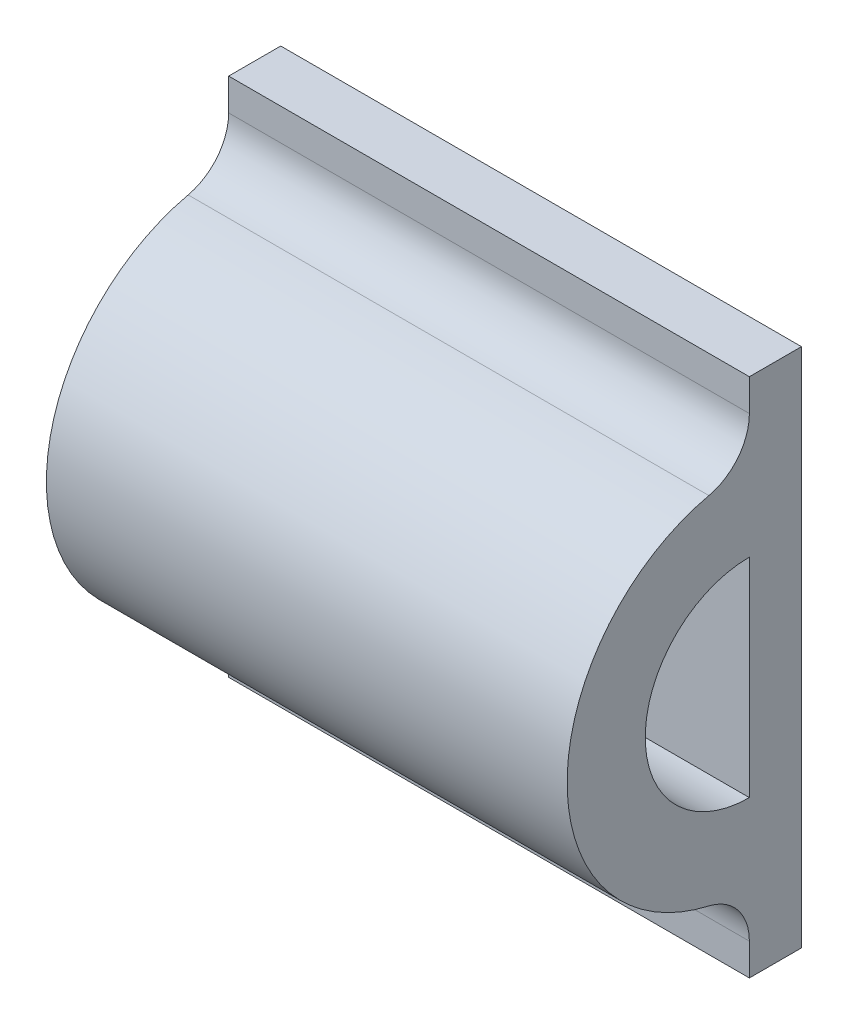
SolidWorks part; units mm, degrees
ref_plane "Alzado" through (0, 0, 0) normal (0, 0, 1) x (1, 0, 0)
ref_plane "Planta" through (0, 0, 0) normal (0, 1, 0) x (1, 0, 0)
ref_plane "Vista lateral" through (0, 0, 0) normal (1, 0, 0) x (0, 0, -1)
sketch "Croquis1" plane through (0, 0, 0) normal (0, 0, 1) x (1, 0, 0)
  line L1 (5, 5) -> (-5, 5)
  line L2 (5, 5) -> (5, -5)
  line L3 (5, -5) -> (-5, -5)
  line L4 (-5, 5) -> (-5, -5)
  line L5 (0, -5) -> (0, 5) construction
  line L6 (5, 0) -> (-5, 0) construction
  point P0 (0, 0)
  dimension "D1" = 10
  dimension "D2" = 10
extrude "Saliente-Extruir1" add sketch "Croquis1" along normal blind 1
sketch "Croquis2" plane through (0, 0, 0) normal (1, 0, 0) x (0, 0, -1)
  line L0 (-1, -5) -> (-1, 5) construction
  line L1 (-1, 3.5) -> (-1, 2)
  line L2 (-1, -2) -> (-1, -3.5)
  arc A0 (-1, -3.5) -> (-1, 3.5) centre (-1, 0) cw
  arc A1 (-1, -2) -> (-1, 2) centre (-1, 0) cw
extrude "Saliente-Extruir2" add sketch "Croquis2" against normal through all from surface at 5 starting at face at (5, 0, 0.5)
fillet "Redondeo2" radius 1 1 edges at (0, 3.5, 1)
fillet "Redondeo3" radius 1 1 edges at (0, -3.5, 1)
